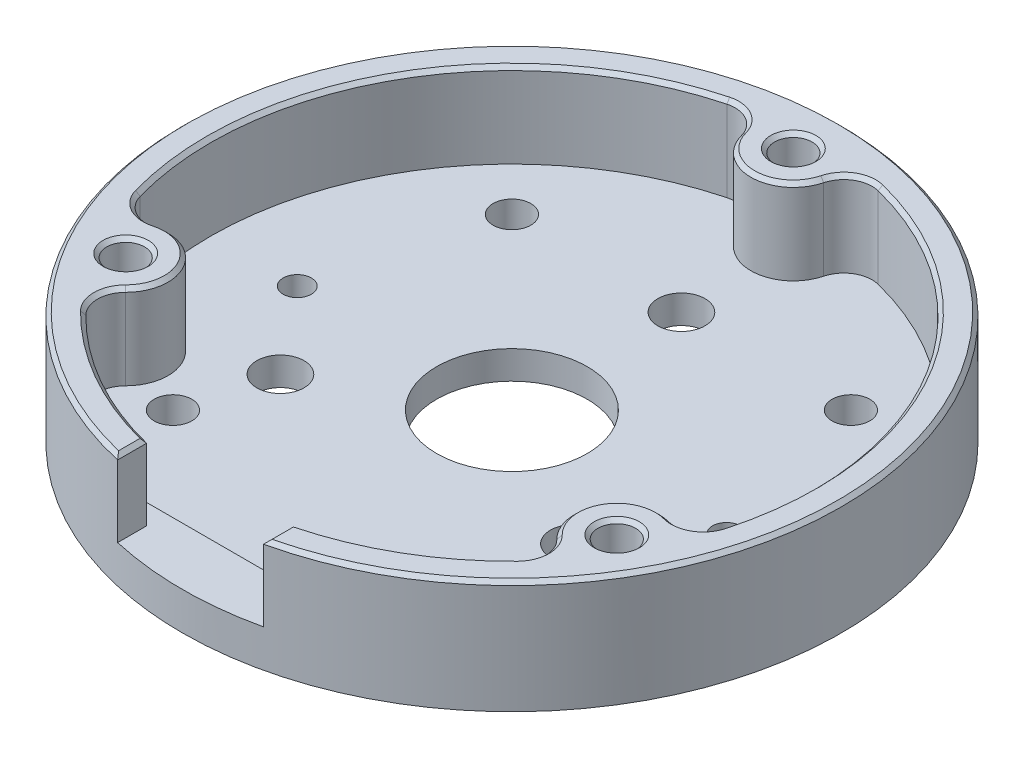
SolidWorks part; units mm, degrees
ref_plane "Спереди" through (0, 0, 0) normal (0, 0, 1) x (1, 0, 0)
ref_plane "Сверху" through (0, 0, 0) normal (0, 1, 0) x (1, 0, 0)
ref_plane "Справа" through (0, 0, 0) normal (1, 0, 0) x (0, 0, -1)
other "Configuration Table"
sketch "Эскиз1" plane through (0, 0, 0) normal (0, 1, 0) x (1, 0, 0)
  circle A0 centre (0, 0) radius 35
  circle A1 centre (0, 0) radius 8
  dimension "D1" = 16
  dimension "D2" = 70
extrude "Бобышка-Вытянуть1" add sketch "Эскиз1" along normal blind 3
sketch "Эскиз2" plane through (0, 3, 0) normal (0, 1, 0) x (1, 0, 0)
  circle A17 centre (-0.1137, 30) radius 2
  circle A18 centre (26.0376, -14.9016) radius 2
  circle A19 centre (-25.9239, -15.0984) radius 2
  circle A21 centre (0, 0) radius 35
  arc A22 (-8.1171, 30.9534) -> (-30.8001, -8.6807) centre (0, 0) ccw
  arc A23 (-4.4591, 28.8309) -> (4.2406, 28.8639) centre (-0.1137, 30) ccw
  arc A24 (27.1979, -10.5537) -> (22.8766, -18.1044) centre (26.0376, -14.9016) ccw
  arc A25 (-22.7387, -18.2772) -> (-27.1171, -10.7595) centre (-25.9239, -15.0984) ccw
  arc A26 (30.865, -8.4471) -> (7.8823, 31.014) centre (0, 0) ccw
  arc A27 (-22.7479, -22.5063) -> (22.9178, -22.3333) centre (0, 0) ccw
  arc A28 (-27.1171, -10.7595) -> (-30.8001, -8.6807) centre (-27.9126, -7.8669) cw
  arc A29 (-22.7387, -18.2772) -> (-22.7479, -22.5063) centre (-20.6153, -20.3964) ccw
  arc A30 (22.8766, -18.1044) -> (22.9178, -22.3333) centre (20.7692, -20.2396) cw
  arc A31 (27.1979, -10.5537) -> (30.865, -8.4471) centre (27.9714, -7.6552) ccw
  arc A32 (-8.1171, 30.9534) -> (-4.4591, 28.8309) centre (-7.3561, 28.0515) cw
  arc A33 (7.8823, 31.014) -> (4.2406, 28.8639) centre (7.1434, 28.1064) ccw
  point P12 (0, 0)
  point P16 (0, 0)
  point P18 (-25.327, -19.5587)
  point P23 (29.6018, -12.1545)
  point P45 (0, 0)
  dimension "D1" = 70
  dimension "D2" = 64
  dimension "D5" = 3
  dimension "D6" = 4
  dimension "D8" = 30
  dimension "D3" = 9
  dimension "D7" = 3
  dimension "D4" = 3
extrude "Бобышка-Вытянуть2" add sketch "Эскиз2" along normal blind 9
sketch "Эскиз3" plane through (0, 3, 0) normal (0, 1, 0) x (1, 0, 0)
  line L0 (0, 0) -> (0, 38.3083) construction
  line L2 (43.0111, 0) -> (0, 0) construction
  circle A0 centre (22.8, 0) radius 1.5
  circle A4 centre (-22.8, 0) radius 1.5
  circle A8 centre (0, 22.8) radius 1.5 [skipped]
  circle A9 centre (-16.122, 16.122) radius 1.5 [skipped]
  circle A10 centre (16.122, 16.122) radius 1.5 [skipped]
  circle A11 centre (-16.122, -16.122) radius 1.5 [skipped]
  circle A12 centre (0, -22.8) radius 1.5 [skipped]
  circle A13 centre (16.122, -16.122) radius 1.5 [skipped]
  point P15 (0, 0)
  dimension "D2" = 3
  dimension "D1" = 90
  dimension "D3" = 22.8
  dimension "D5" = 22.8
  dimension "D4" = 8
extrude "Вырез-Вытянуть1" cut sketch "Эскиз3" against normal blind 8
sketch "Эскиз4" plane through (0, 3, 0) normal (0, 1, 0) x (1, 0, 0)
  line L0 (0, 18) -> (0, 0) construction
  circle A0 centre (0, 18) radius 2.5064
  circle A1 centre (15.5885, -9) radius 2.5064
  circle A2 centre (-15.5885, -9) radius 2.5064
  point P15 (0, 0)
  dimension "D2" = 18
  dimension "D3" = 3
extrude "Вырез-Вытянуть2" cut sketch "Эскиз4" against normal blind 8
sketch "Эскиз5" plane through (0, 3, 0) normal (0, 1, 0) x (1, 0, 0)
  line L1 (-12.0085, 30.9047) -> (-30.9047, 12.0085)
  arc A0 (-30.9047, 12.0085) -> (-12.0085, 30.9047) centre (0, 0) cw
extrude "Бобышка-Вытянуть3" [suppressed] add sketch "Эскиз5" along normal blind 1
sketch "Эскиз7" plane through (0, 3, 0) normal (0, 1, 0) x (1, 0, 0)
  circle A0 centre (-18, -18) radius 2
  circle A1 centre (18, -18) radius 2
  circle A2 centre (-18, 18) radius 2
  circle A3 centre (18, 18) radius 2
  dimension "D1" = 4
  dimension "D2" = 4
  dimension "D5" = 4
  dimension "D6" = 4
  dimension "D3" = 18
  dimension "D4" = 18
  dimension "D7" = 18
  dimension "D8" = 18
  dimension "D9" = 18
  dimension "D10" = 18
extrude "Вырез-Вытянуть4" cut sketch "Эскиз7" against normal blind 12
sketch "Эскиз8" plane through (0, 3, 0) normal (0, 1, 0) x (1, 0, 0)
  line L0 (-13.7488, -28.8958) -> (13.7488, -28.8958)
  arc A0 (-22.7479, -22.5063) -> (22.9178, -22.3333) centre (0, 0) ccw construction
  arc A1 (-13.7488, -28.8958) -> (13.7488, -28.8958) centre (0, 0) ccw
extrude "Бобышка-Вытянуть4" add sketch "Эскиз8" along normal blind 1
sketch "Эскиз9" plane through (0, 0, 28.8958) normal (0, 0, -1) x (-1, 0, 0)
  line L0 (-13.7488, 4) -> (13.7488, 4) construction
  line L1 (-7.7488, 4) -> (7.7488, 4)
  line L2 (-7.7488, 4) -> (-7.7488, 13.4818)
  line L3 (-7.7488, 13.4818) -> (7.7488, 13.4818)
  line L4 (7.7488, 4) -> (7.7488, 13.4818)
  line L5 (13.7488, 4) -> (13.7488, 3) construction
  dimension "D1" = 6
  dimension "D2" = 6
  dimension "D3" = 15.4977
extrude "Вырез-Вытянуть5" cut sketch "Эскиз9" against normal blind 11
sketch "Эскиз10" plane through (0, 3, 0) normal (0, 1, 0) x (1, 0, 0)
  circle A0 centre (0, 0) radius 22.5 construction
  dimension "D1" = 45
chamfer "Фаска1" distance 0.4 angle 45 19 edges at (-25.9239, 12, 17.0984) (-0.1137, 12, -28) (26.0376, 12, 16.9016) (15.9403, 12, 27.7472) (23.7691, 12, 20.2103) (22.132, 12, 12.6663) (29.4658, 12, 10.2565) (27.652, 12, -16.1049) (5.6181, 12, -30.6898) (-0.0966, 12, -25.5) (-5.8505, 12, -30.6463) (-27.7732, 12, -15.8949) (-29.3872, 12, 10.4794) (-22.0354, 12, 12.8337) (-23.6152, 12, 20.3899) (-15.8351, 12, 27.8074) (-7.7488, 12, 32.5895) (0, 12, -35) (7.7488, 12, 32.5895)
equation "\"22б5\"=23.4905"
